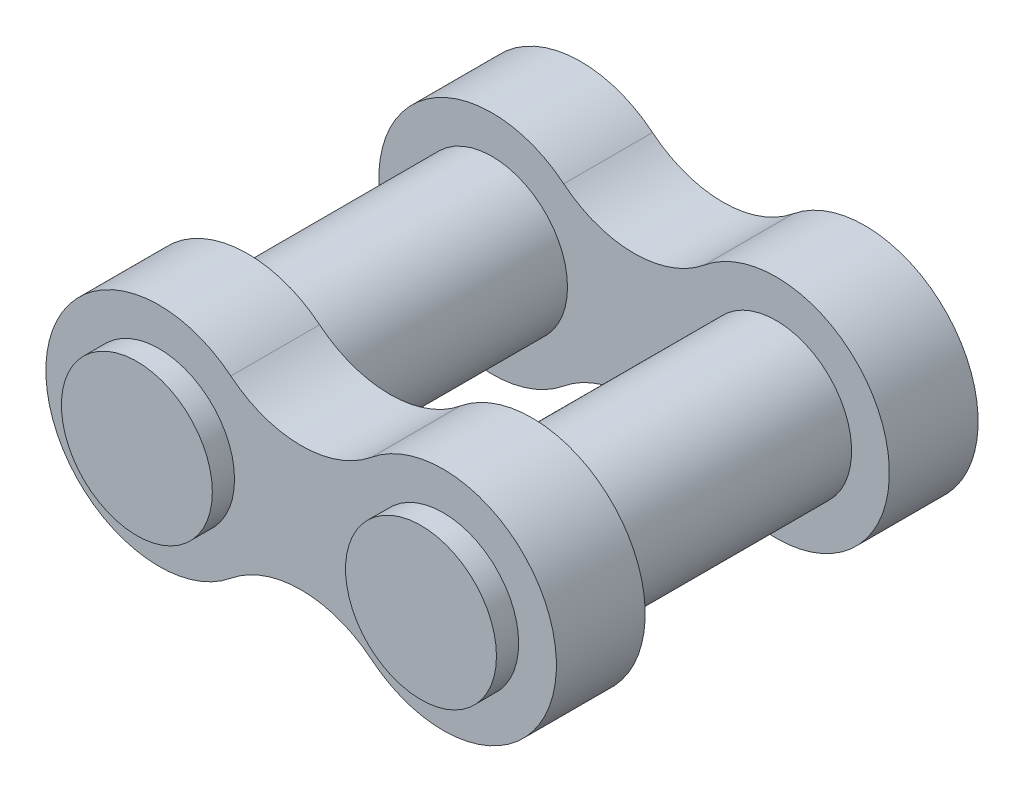
SolidWorks part; units mm, degrees
material "AISI 304"
ref_plane "Alzado" through (0, 0, 0) normal (0, 0, 1) x (1, 0, 0)
ref_plane "Planta" through (0, 0, 0) normal (0, 1, 0) x (1, 0, 0)
ref_plane "Vista lateral" through (0, 0, 0) normal (1, 0, 0) x (0, 0, -1)
sketch "Croquis1" plane through (0, 0, 0) normal (0, 0, 1) x (1, 0, 0)
  line L0 (0, 18.4869) -> (0, 1.4067) construction
  line L1 (-24.1051, 0) -> (21.976, 0) construction
  line L2 (0, -1.4067) -> (0, -17.3193) construction
  arc A0 (-1.5842, 1.9727) -> (-1.5842, -1.9727) centre (-3.2, 0) ccw
  circle A1 centre (-3.2, 0) radius 1.7
  circle A2 centre (3.2, 0) radius 1.7
  arc A3 (1.5842, 1.9727) -> (1.5842, -1.9727) centre (3.2, 0) cw
  arc A4 (-1.5842, 1.9727) -> (1.5842, 1.9727) centre (0, 3.9067) ccw
  arc A5 (-1.5842, -1.9727) -> (1.5842, -1.9727) centre (0, -3.9067) cw
  point P17 (0, 3.7835)
  dimension "D1" = 5.1
  dimension "D2" = 3.4
  dimension "D4" = 2.5
  dimension "D3" = 6.4
extrude "Saliente-Extruir1" add sketch "Croquis1" along normal blind 2
sketch "Croquis3" plane through (0, 0, 2) normal (0, 0, 1) x (1, 0, 0)
  circle A1 centre (-3.2, 0) radius 1.7
  circle A2 centre (-3.2, 0) radius 1.7
  circle A3 centre (3.2, 0) radius 1.7
  circle A4 centre (3.2, 0) radius 1.7
  dimension "D1" = 0
  dimension "D2" = 0
extrude "Saliente-Extruir2" add sketch "Croquis3" along normal blind 8 and the other way blind 2.5
ref_plane "Plano1" through (0, 0, 4.75) normal (0, 0, 1) x (1, 0, 0)
mirror "Simetría1" about plane through (0, 0, 4.75) normal (0, 0, 1) of "Saliente-Extruir1"
